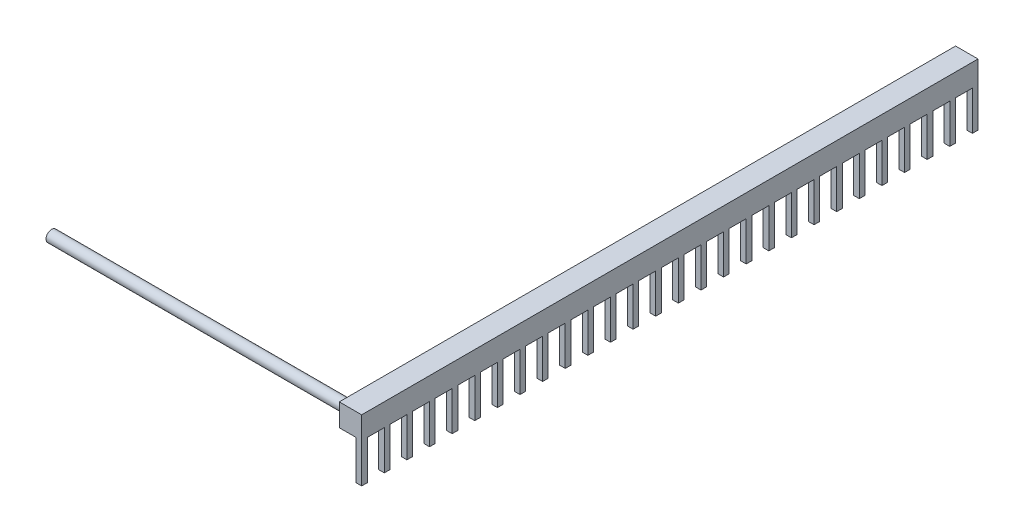
SolidWorks part; units mm, degrees
ref_plane "Front Plane" through (0, 0, 0) normal (0, 0, 1) x (1, 0, 0)
ref_plane "Top Plane" through (0, 0, 0) normal (0, 1, 0) x (1, 0, 0)
ref_plane "Right Plane" through (0, 0, 0) normal (1, 0, 0) x (0, 0, -1)
sketch "Sketch1" plane through (0, 0, 0) normal (0, 0, 1) x (1, 0, 0)
  line L1 (0, 0) -> (-20, 0)
  line L2 (0, 0) -> (0, 20)
  line L3 (0, 20) -> (-20, 20)
  line L4 (-20, 0) -> (-20, 20)
  dimension "D1" = 20
extrude "Boss-Extrude1" add sketch "Sketch1" along normal blind 550
sketch "Sketch2" plane through (-20, 0, 0) normal (-1, 0, 0) x (0, 0, 1)
  line L0 (550, 20) -> (0, 20) construction
  line L1 (550, 0) -> (530, 0)
  line L2 (550, 0) -> (550, 20)
  line L3 (550, 20) -> (530, 20)
  line L4 (530, 0) -> (530, 20)
  line L5 (530, 20) -> (550, 0)
  circle A0 centre (540, 10) radius 5
  dimension "D1" = 10
extrude "Boss-Extrude2" add sketch "Sketch2" along normal blind 266.7 contours A0
sketch "Sketch3" plane through (0, 0, 550) normal (0, 0, 1) x (1, 0, 0)
  line L1 (0, 0) -> (-5, 0)
  line L2 (0, 0) -> (0, -35)
  line L3 (0, -35) -> (-5, -35)
  line L4 (-5, 0) -> (-5, -35)
  dimension "D1" = 5
  dimension "D2" = 35
extrude "Boss-Extrude3" add sketch "Sketch3" against normal blind 5
pattern_linear "LPattern1" count 28 spacing 20.1852 along (0, 0, -1) of "Boss-Extrude3"
